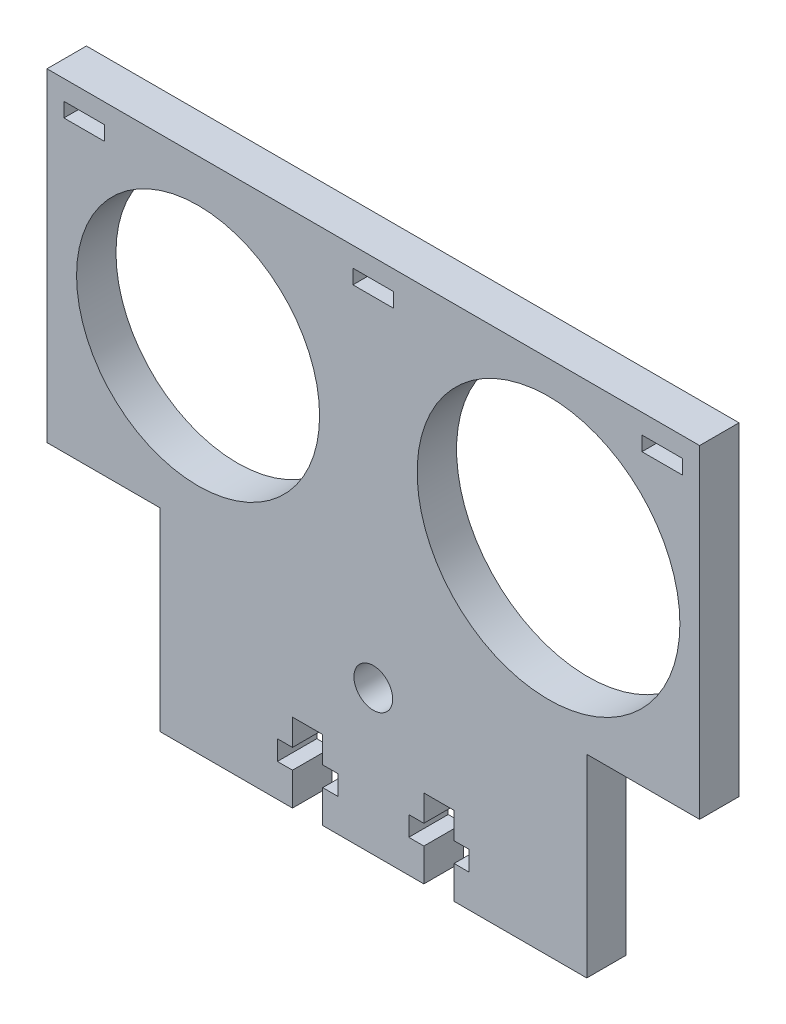
SolidWorks part; units mm, degrees
material "ABS"
ref_plane "Front Plane" through (0, 0, 0) normal (0, 0, 1) x (1, 0, 0)
ref_plane "Top Plane" through (0, 0, 0) normal (0, 1, 0) x (1, 0, 0)
ref_plane "Right Plane" through (0, 0, 0) normal (1, 0, 0) x (0, 0, -1)
sketch "Sketch1" plane through (0, 0, 0) normal (0, 0, 1) x (1, 0, 0)
  line L0 (0, 0) -> (-26.6757, 31.7908) construction
  line L1 (0, 0) -> (0, 56.7908) construction
  line L2 (-32.5, 7.5) -> (-32.5, -22)
  line L3 (-32.5, -22) -> (32.5, -22)
  line L4 (32.5, -22) -> (32.5, 7.5)
  line L5 (0, 0) -> (0, -22) construction
  line L6 (0, 0) -> (26.6757, 31.7908) construction
  line L10 (-32.5, 7.5) -> (-49.6757, 7.5)
  line L11 (-49.6757, 7.5) -> (-49.6757, 56.7908)
  line L12 (-49.6757, 56.7908) -> (49.6757, 56.7908)
  line L13 (49.6757, 56.7908) -> (49.6757, 7.5)
  line L14 (49.6757, 7.5) -> (32.5, 7.5)
  circle A0 centre (0, 0) radius 2.95
  circle A1 centre (26.6757, 31.7908) radius 20
  circle A2 centre (-26.6757, 31.7908) radius 18.5
  dimension "D1" = 5.9
  dimension "D9" = 37
  dimension "D11" = 40
  dimension "D2" = 41.5
  dimension "D4" = 40
  dimension "D5" = 22
  dimension "D6" = 65
  dimension "D3" = 23
  dimension "D7" = 25
  dimension "D8" = 29.5
  dimension "D10" = 40
extrude "Boss-Extrude1" add sketch "Sketch1" along normal blind 6
sketch "Sketch3" plane through (0, 0, 6) normal (0, 0, 1) x (1, 0, 0)
  line L0 (-32.5, -22) -> (32.5, -22) construction
  line L1 (-12.3, -22) -> (-7.7, -22)
  line L2 (-12.3, -22) -> (-12.3, -17)
  line L3 (-12.3, -10) -> (-7.7, -10)
  line L4 (-7.7, -22) -> (-7.7, -17)
  line L5 (0, 0) -> (0, -22) construction
  line L6 (-7.7, -14) -> (-5.4, -14)
  line L7 (-14.6, -14) -> (-12.3, -14)
  line L8 (-14.6, -14) -> (-14.6, -17)
  line L9 (-14.6, -17) -> (-12.3, -17)
  line L10 (-5.4, -14) -> (-5.4, -17)
  line L11 (-12.3, -14) -> (-12.3, -10)
  line L12 (-7.7, -17) -> (-5.4, -17)
  line L13 (-7.7, -14) -> (-7.7, -10)
  line L14 (7.7, -14) -> (7.7, -10)
  line L15 (7.7, -17) -> (5.4, -17)
  line L16 (12.3, -14) -> (12.3, -10)
  line L17 (5.4, -14) -> (5.4, -17)
  line L18 (14.6, -17) -> (12.3, -17)
  line L19 (14.6, -14) -> (14.6, -17)
  line L20 (14.6, -14) -> (12.3, -14)
  line L21 (7.7, -14) -> (5.4, -14)
  line L22 (7.7, -22) -> (7.7, -17)
  line L23 (12.3, -10) -> (7.7, -10)
  line L24 (12.3, -22) -> (12.3, -17)
  line L25 (12.3, -22) -> (7.7, -22)
  point P6 (-10, -10)
  point P18 (-13.45, -17)
  dimension "D1" = 4.6
  dimension "D2" = 10
  dimension "D3" = 12
  dimension "D4" = 9.2
  dimension "D5" = 3
  dimension "D6" = 5
extrude "Cut-Extrude2" cut sketch "Sketch3" against normal through all
sketch "Sketch4" plane through (0, 0, 6) normal (0, 0, 1) x (1, 0, 0)
  line L1 (3.1, 53.7908) -> (-3.1, 53.7908)
  line L2 (3.1, 53.7908) -> (3.1, 51.5908)
  line L3 (3.1, 51.5908) -> (-3.1, 51.5908)
  line L4 (-3.1, 53.7908) -> (-3.1, 51.5908)
  line L5 (47.1, 53.7908) -> (40.9, 53.7908)
  line L6 (47.1, 53.7908) -> (47.1, 51.5908)
  line L7 (47.1, 51.5908) -> (40.9, 51.5908)
  line L8 (40.9, 53.7908) -> (40.9, 51.5908)
  line L9 (-40.9, 53.7908) -> (-47.1, 53.7908)
  line L10 (-40.9, 53.7908) -> (-40.9, 51.5908)
  line L11 (-40.9, 51.5908) -> (-47.1, 51.5908)
  line L12 (-47.1, 53.7908) -> (-47.1, 51.5908)
extrude "Cut-Extrude3" cut sketch "Sketch4" against normal through all
equation "\"smallPulleyTeeth\"= 30"
equation "\"largePulleyTeeth\"= 30"
equation "\"eighthThick\"= 3.0mm"
equation "\"sixteenthThick\" = 1.7mm"
equation "\"quarterThick\"=6.0mm"
equation "\"OD\" = 145mm"
equation "\"puckAngle\" = 60.5deg"
equation "\"puckDiam\" = 76.5mm"
equation "\"axlePress\" = 5.9mm"
equation "\"D1@Sketch1\"=\"axlePress\""
equation "\"D1@Boss-Extrude1\"=\"quarterThick\""
equation "\"press\" = 0.2mm"
equation "\"wheelClear\" = 0.3mm"
equation "\"10-32clear\" = 4.8mm"
equation "\"D1@Sketch3\"=\"10-32clear\"-\"press\""
equation "\"6-32clear\" = 3.3mm"
equation "\"8-32clear\" = 4.0mm"
equation "\"wheelHeight\" = 22mm"
equation "\"D5@Sketch1\"=\"wheelHeight\""
equation "\"4-40clear\" = 3.0mm"
equation "\"wheelWell\" = 65mm"
equation "\"D6@Sketch1\"=\"wheelWell\""
equation "\"D8@Sketch1\"=\"eighthThick\"*10-0.5"
